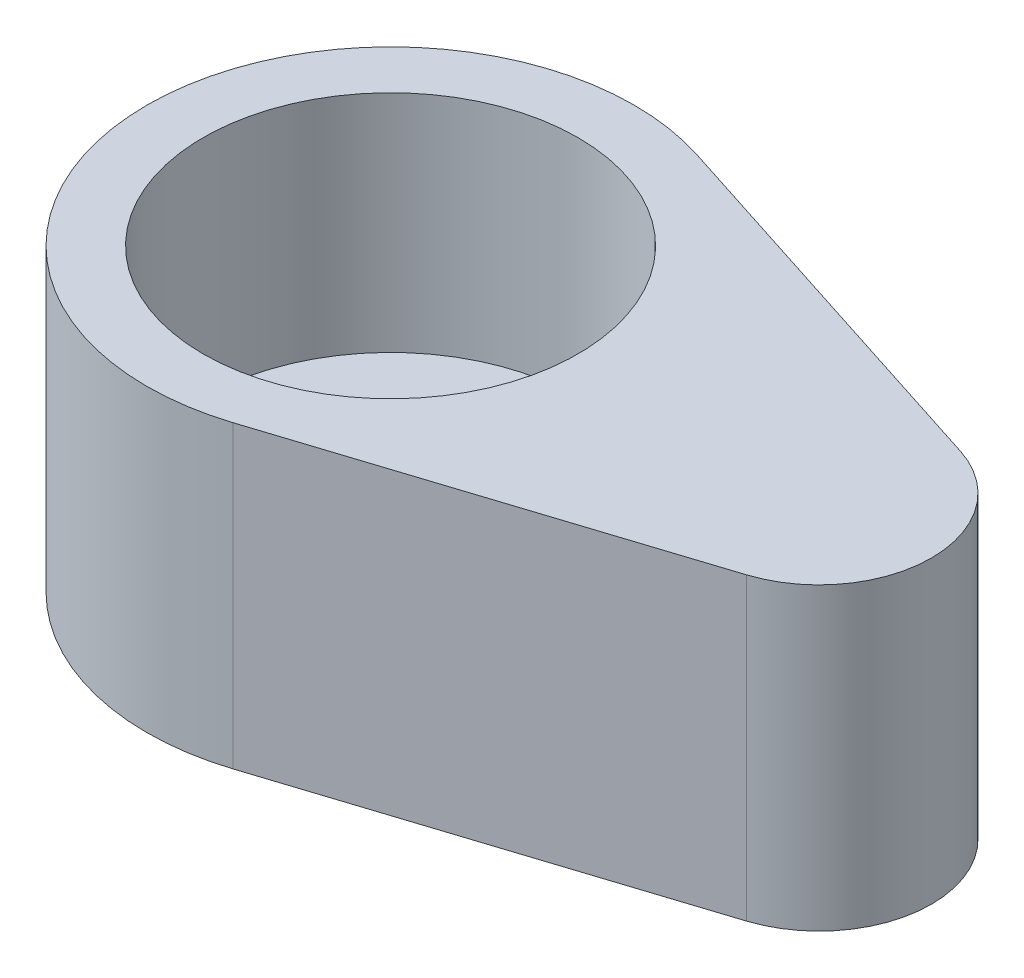
SolidWorks part; units mm, degrees
ref_plane "Front Plane" through (0, 0, 0) normal (0, 0, 1) x (1, 0, 0)
ref_plane "Top Plane" through (0, 0, 0) normal (0, 1, 0) x (1, 0, 0)
ref_plane "Right Plane" through (0, 0, 0) normal (1, 0, 0) x (0, 0, -1)
sketch "Sketch1" plane through (0, 0, 0) normal (0, 1, 0) x (1, 0, 0)
  line L0 (1.9904, -6.1878) -> (12.3486, -2.8559)
  line L1 (12.3486, 2.8559) -> (1.9904, 6.1878)
  circle A0 centre (0, 0) radius 6.5
  arc A1 (12.3486, -2.8559) -> (12.3486, 2.8559) centre (11.43, 0) ccw
  dimension "D1" = 13
  dimension "D3" = 3
  dimension "D2" = 11.43
extrude "Boss-Extrude1" add sketch "Sketch1" along normal blind 8 contours A0 | L0 A1 L1 A0
sketch "Sketch2" plane through (0, 8, 0) normal (0, 1, 0) x (1, 0, 0)
  circle A0 centre (0, 0) radius 5
  dimension "D1" = 10
extrude "Cut-Extrude1" cut sketch "Sketch2" against normal blind 6
